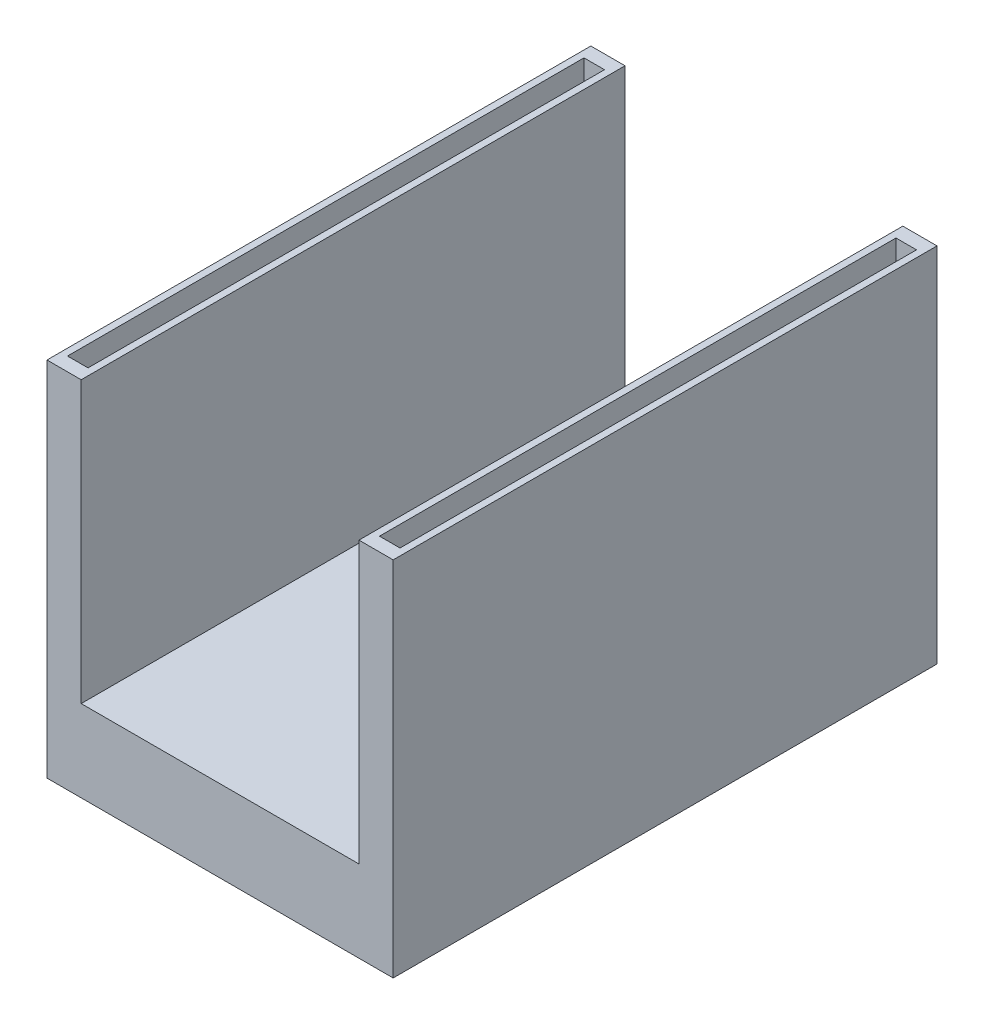
SolidWorks part; units mm, degrees
ref_plane "Front Plane" through (0, 0, 0) normal (0, 0, 1) x (1, 0, 0)
ref_plane "Top Plane" through (0, 0, 0) normal (0, 1, 0) x (1, 0, 0)
ref_plane "Right Plane" through (0, 0, 0) normal (1, 0, 0) x (0, 0, -1)
sketch "Sketch3" plane through (0, 0, 0) normal (0, 0, 1) x (1, 0, 0)
  line L0 (0, 0) -> (0, 105.8703)
  line L1 (0, 105.8703) -> (10, 105.8703)
  line L2 (10, 105.8703) -> (10, 23.8728)
  line L3 (10, 23.8728) -> (91.2129, 23.8728)
  line L4 (91.2129, 23.8728) -> (91.2129, 105.8703)
  line L5 (91.2129, 105.8703) -> (101.2129, 105.8703)
  line L6 (101.2129, 105.8703) -> (101.2129, 0)
  line L7 (101.2129, 0) -> (0, 0)
  dimension "D1" = 10
  dimension "D2" = 10
  dimension "D3" = 81.2129
  dimension "D4" = 23.8728
  dimension "D5" = 105.8703
extrude "Boss-Extrude2" add sketch "Sketch3" along normal blind 159
sketch "Sketch4" plane through (0, 105.8703, 0) normal (0, 1, 0) x (1, 0, 0)
  line L0 (10, -159) -> (10, 0) construction
  line L1 (2, -4) -> (8, -4)
  line L2 (2, -4) -> (2, -155)
  line L3 (2, -155) -> (8, -155)
  line L4 (8, -4) -> (8, -155)
  line L5 (93.2129, -4) -> (99.2129, -4)
  line L6 (93.2129, -4) -> (93.2129, -155)
  line L7 (93.2129, -155) -> (99.2129, -155)
  line L8 (99.2129, -4) -> (99.2129, -155)
  line L9 (101.2129, -159) -> (101.2129, 0) construction
  line L10 (10, 0) -> (0, 0) construction
  line L11 (101.2129, 0) -> (91.2129, 0) construction
  line L12 (101.2129, -159) -> (91.2129, -159) construction
  line L13 (10, -159) -> (0, -159) construction
  point P18 (5, -159)
  dimension "D1" = 6
  dimension "D2" = 6
  dimension "D3" = 2
  dimension "D4" = 2
  dimension "D5" = 4
  dimension "D6" = 4
  dimension "D7" = 4
  dimension "D8" = 4
extrude "Cut-Extrude1" cut sketch "Sketch4" against normal blind 20
